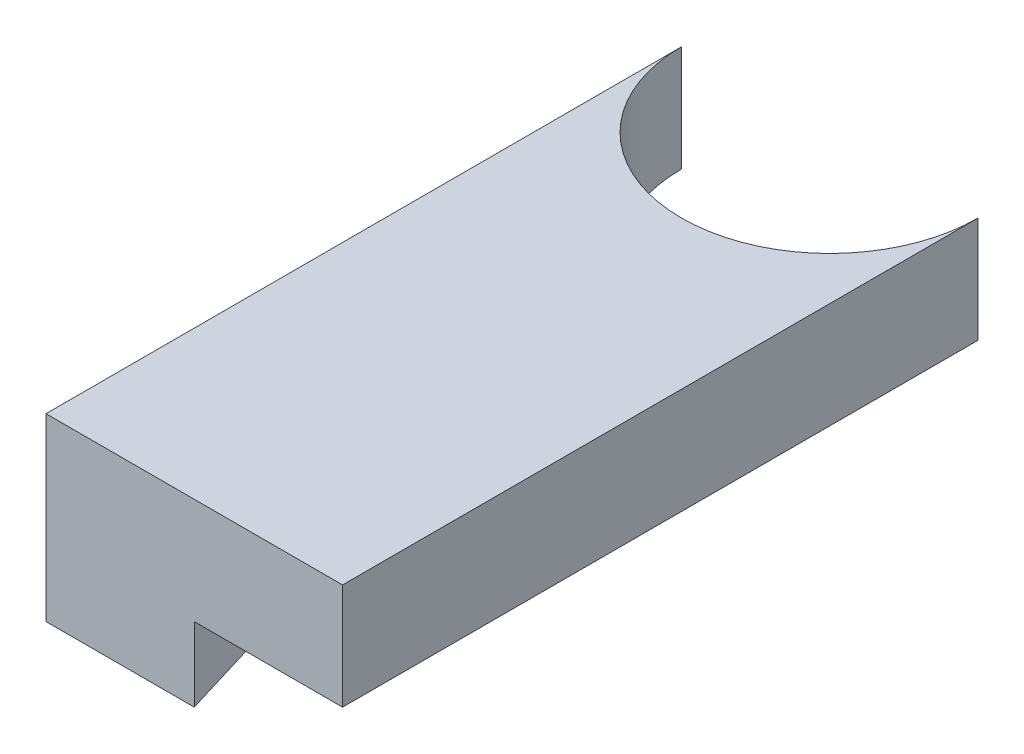
SolidWorks part; units mm, degrees
ref_plane "Front Plane" through (0, 0, 0) normal (0, 0, 1) x (1, 0, 0)
ref_plane "Top Plane" through (0, 0, 0) normal (0, 1, 0) x (1, 0, 0)
ref_plane "Right Plane" through (0, 0, 0) normal (1, 0, 0) x (0, 0, -1)
sketch "Sketch1" plane through (0, 0, 0) normal (0, 1, 0) x (1, 0, 0)
  line L0 (0, 15.24) -> (0, 0)
  line L1 (0, 0) -> (7.112, 0)
  line L2 (7.112, 0) -> (7.112, 15.24)
  arc A0 (7.112, 15.24) -> (0, 15.24) centre (3.556, 15.24) cw
  dimension "D1" = 7.112
  dimension "D2" = 15.24
extrude "Boss-Extrude1" add sketch "Sketch1" along normal blind 2.54
sketch "Sketch2" plane through (0, 0, 0) normal (0, -1, 0) x (1, 0, 0)
  line L0 (0, 0) -> (3.556, 0)
  line L1 (0, 0) -> (7.112, 0) construction
  line L2 (3.556, 0) -> (0, -11.684)
  line L3 (0, -15.24) -> (0, 0) construction
  line L4 (0, -11.684) -> (0, 0)
  arc A0 (7.112, -15.24) -> (0, -15.24) centre (3.556, -15.24) ccw construction
  point P12 (3.556, -11.684)
extrude "Boss-Extrude2" add sketch "Sketch2" along normal blind 1.778
